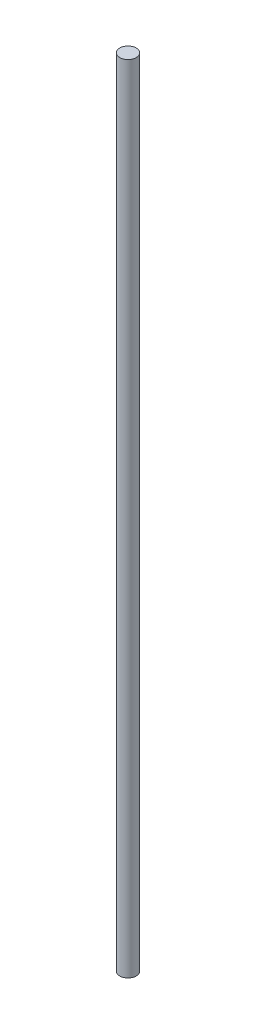
SolidWorks part; units mm, degrees
ref_plane "Front Plane" through (0, 0, 0) normal (0, 0, 1) x (1, 0, 0)
ref_plane "Top Plane" through (0, 0, 0) normal (0, 1, 0) x (1, 0, 0)
ref_plane "Right Plane" through (0, 0, 0) normal (1, 0, 0) x (0, 0, -1)
sketch "Sketch1" plane through (0, 0, 0) normal (0, 1, 0) x (1, 0, 0)
  circle A0 centre (0, 0) radius 9.525
extrude "Boss-Extrude1" add sketch "Sketch1" along normal blind 914.4
